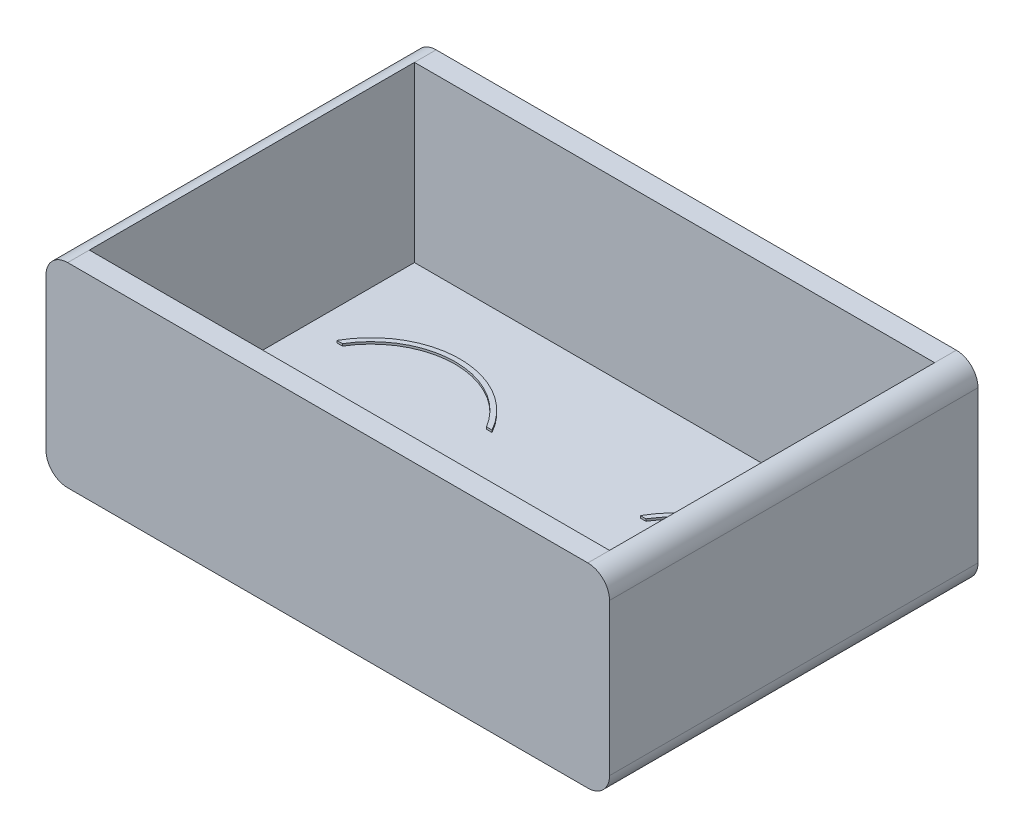
SolidWorks part; units mm, degrees
ref_plane "Front Plane" through (0, 0, 0) normal (0, 0, 1) x (1, 0, 0)
ref_plane "Top Plane" through (0, 0, 0) normal (0, 1, 0) x (1, 0, 0)
ref_plane "Right Plane" through (0, 0, 0) normal (1, 0, 0) x (0, 0, -1)
sketch "Sketch1" plane through (0, 0, 0) normal (0, 0, 1) x (1, 0, 0)
  line L0 (-140.4249, 0) -> (140.4249, 0) construction
  line L1 (0, 77.8755) -> (0, -77.8755) construction
  line L2 (-130, 45) -> (130, 45)
  line L3 (-130, -45) -> (130, -45)
  line L4 (-130, -45) -> (-130, 45)
  line L5 (130, 45) -> (130, -45)
  point P4 (0, 0)
  point P8 (0, 0)
  point P11 (0, 45)
  dimension "D1" = 260
  dimension "D2" = 90
extrude "Boss-Extrude1" add sketch "Sketch1" along normal blind 10
sketch "Sketch2" plane through (0, 0, 10) normal (0, 0, 1) x (1, 0, 0)
  line L0 (-130, 45) -> (-130, -45)
  line L1 (-130, -45) -> (130, -45) construction
  line L2 (-130, 45) -> (-130, -45) construction
  line L3 (-130, -45) -> (130, -45)
  line L4 (130, -45) -> (130, 45)
  line L5 (130, 45) -> (120, 45)
  line L6 (130, 45) -> (-130, 45) construction
  line L7 (120, 45) -> (120, -35)
  line L8 (120, -35) -> (-120, -35)
  line L9 (-120, -35) -> (-120, 45)
  line L10 (-120, 45) -> (-130, 45)
  dimension "D1" = 10
  dimension "D2" = 10
extrude "Boss-Extrude2" add sketch "Sketch2" along normal blind 160
sketch "Sketch3" plane through (0, -35, 0) normal (0, 1, 0) x (1, 0, 0)
  line L0 (-120, -170) -> (-120, -160)
  line L1 (-120, -170) -> (-120, -10) construction
  line L2 (-120, -160) -> (120, -160)
  line L3 (120, -170) -> (120, -10) construction
  line L4 (120, -160) -> (120, -170)
  line L5 (120, -170) -> (-120, -170)
  dimension "D1" = 10
extrude "Boss-Extrude3" add sketch "Sketch3" along normal blind 80
sketch "Sketch4" plane through (0, 0, 0) normal (0, 0, -1) x (-1, 0, 0)
  line L0 (-40, 0) -> (40, 0) construction
  circle A0 centre (-40, 0) radius 5
  circle A1 centre (40, 0) radius 5
  point P4 (0, 0)
  dimension "D1" = 10
  dimension "D2" = 10
  dimension "D3" = 80
extrude "Boss-Extrude4" add sketch "Sketch4" along normal blind 15
sketch "Sketch5" plane through (0, 0, -15) normal (0, 0, -1) x (-1, 0, 0)
  line L0 (-78.5508, 0) -> (78.5508, 0) construction
  line L1 (0, -7.5) -> (0, 7.5) construction
  line L2 (-45, 7.5) -> (45, 7.5)
  line L3 (50, 2.5) -> (50, -2.5)
  line L4 (45, -7.5) -> (-45, -7.5)
  line L5 (-50, -2.5) -> (-50, 2.5)
  arc A0 (45, 7.5) -> (50, 2.5) centre (45, 2.5) cw
  arc A1 (50, -2.5) -> (45, -7.5) centre (45, -2.5) cw
  arc A2 (-45, -7.5) -> (-50, -2.5) centre (-45, -2.5) cw
  arc A3 (-45, 7.5) -> (-50, 2.5) centre (-45, 2.5) ccw
  point P4 (0, 0)
  point P7 (0, 0)
  point P10 (0, 7.5)
  point P15 (50, 7.5)
  point P18 (50, -7.5)
  point P23 (-50, 7.5)
  dimension "D3" = 5
  dimension "D1" = 100
  dimension "D2" = 15
extrude "Boss-Extrude5" add sketch "Sketch5" along normal blind 5
sketch "Sketch6" plane through (0, 0, -20) normal (0, 0, -1) x (-1, 0, 0)
  line L0 (0, 0) -> (0, -3) construction
  line L1 (-42.6107, -3) -> (42.6107, -3) construction
  text T0 "Storage" font "Century Gothic" height in points 26
  point P6 (0, -3)
  dimension "D1" = 3
extrude "Boss-Extrude6" add sketch "Sketch6" along normal blind 1
sketch "Sketch7" plane through (0, -35, 0) normal (0, 1, 0) x (1, 0, 0)
  line L0 (-34.2089, -60) -> (-36.7726, -60)
  line L1 (-103.2274, -60) -> (-105.7911, -60)
  line L2 (0, 0) -> (0, -144.8551) construction
  line L3 (103.2274, -60) -> (105.7911, -60)
  line L4 (34.2089, -60) -> (36.7726, -60)
  arc A0 (-36.7726, -60) -> (-103.2274, -60) centre (-70, -80) ccw
  arc A1 (-34.2089, -60) -> (-105.7911, -60) centre (-70, -80) ccw
  arc A2 (34.2089, -60) -> (105.7911, -60) centre (70, -80) cw
  arc A3 (36.7726, -60) -> (103.2274, -60) centre (70, -80) cw
  dimension "D1" = 77.5644
  dimension "D4" = 82
  dimension "D2" = 70
  dimension "D3" = 80
  dimension "D5" = 60
extrude "Boss-Extrude7" add sketch "Sketch7" along normal blind 1
sketch "Sketch9" plane through (0, 0, 0) normal (0, 0, -1) x (-1, 0, 0)
  line L4 (-130, 35) -> (-130, 45)
  line L5 (-130, 45) -> (-120, 45)
  line L6 (120, 45) -> (130, 45)
  line L7 (130, 45) -> (130, 35)
  line L8 (120, -45) -> (130, -45)
  line L9 (130, -45) -> (130, -35)
  line L10 (-130, -35) -> (-130, -45)
  line L11 (-130, -45) -> (-120, -45)
  line L12 (-130, 35) -> (-120, 35) construction
  line L13 (-120, 35) -> (-120, 45) construction
  line L14 (120, -45) -> (120, -35) construction
  line L15 (120, -35) -> (130, -35) construction
  arc A0 (130, 35) -> (120, 45) centre (120, 35) ccw
  arc A1 (120, -45) -> (130, -35) centre (120, -35) ccw
  arc A2 (-130, -35) -> (-120, -45) centre (-120, -35) ccw
  arc A3 (-130, 35) -> (-120, 45) centre (-120, 35) cw
  point P10 (130, 45)
  point P13 (130, -45)
  point P16 (-130, -45)
  point P19 (-130, 45)
  dimension "D1" = 10
extrude "Cut-Extrude1" cut sketch "Sketch9" against normal blind 209
